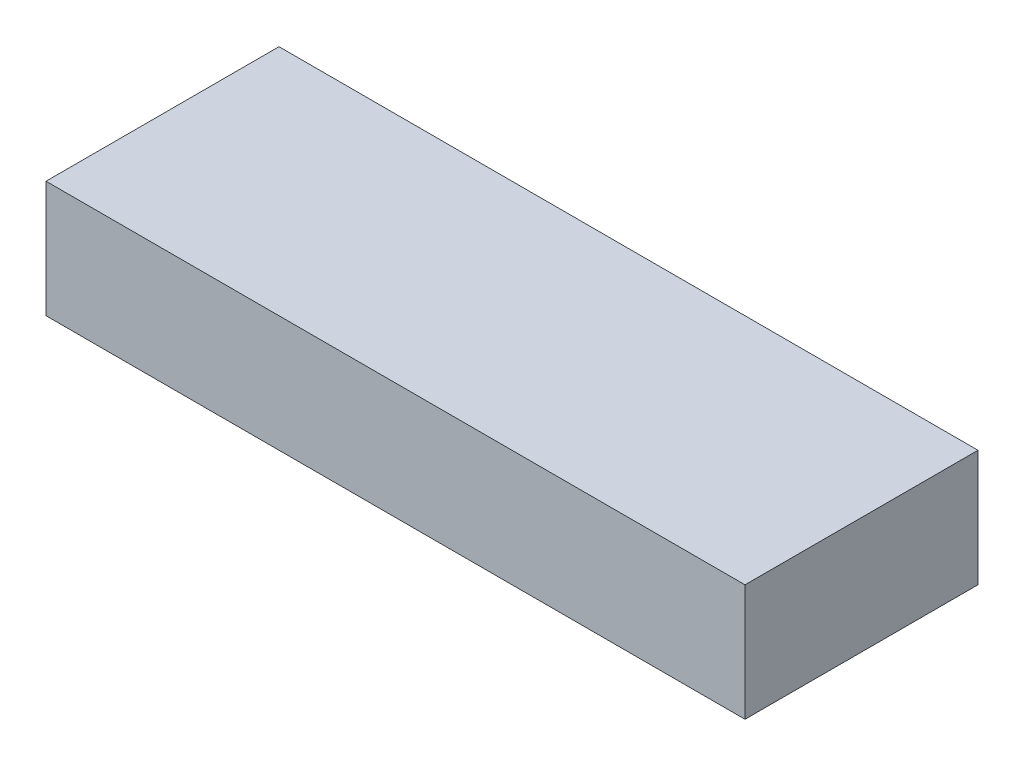
SolidWorks part; units mm, degrees
material "Oak"
ref_plane "Front Plane" through (0, 0, 0) normal (0, 0, 1) x (1, 0, 0)
ref_plane "Top Plane" through (0, 0, 0) normal (0, 1, 0) x (1, 0, 0)
ref_plane "Right Plane" through (0, 0, 0) normal (1, 0, 0) x (0, 0, -1)
sketch "Sketch1" plane through (0, 0, 0) normal (0, 1, 0) x (1, 0, 0)
  line L1 (-38.1, -12.7) -> (38.1, -12.7)
  line L2 (-38.1, -12.7) -> (-38.1, 12.7)
  line L3 (-38.1, 12.7) -> (38.1, 12.7)
  line L4 (38.1, -12.7) -> (38.1, 12.7)
  line L5 (-38.1, -12.7) -> (38.1, 12.7) construction
  line L6 (-38.1, 12.7) -> (38.1, -12.7) construction
  point P0 (0, 0)
  dimension "D1" = 76.2
  dimension "D2" = 25.4
extrude "Boss-Extrude1" add sketch "Sketch1" along normal mid plane 12.7
